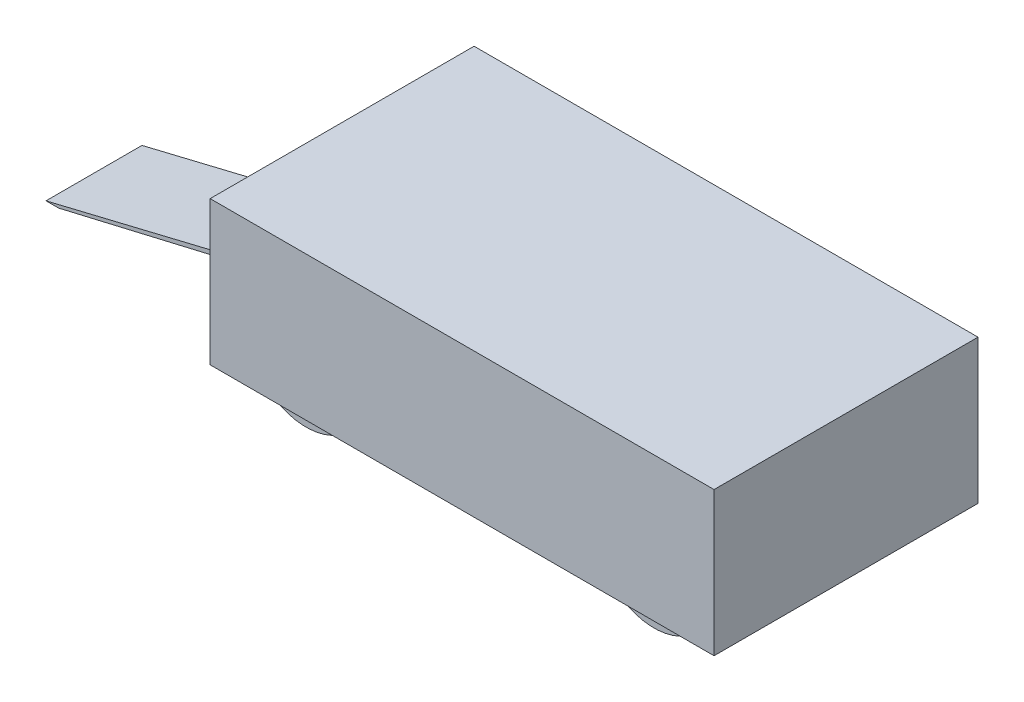
SolidWorks part; units mm, degrees
ref_plane "Front Plane" through (0, 0, 0) normal (0, 0, 1) x (1, 0, 0)
ref_plane "Top Plane" through (0, 0, 0) normal (0, 1, 0) x (1, 0, 0)
ref_plane "Right Plane" through (0, 0, 0) normal (1, 0, 0) x (0, 0, -1)
sketch "Chasis" plane through (0, 0, 0) normal (0, 1, 0) x (1, 0, 0)
  line L1 (-266.7, -139.7) -> (266.7, -139.7)
  line L2 (-266.7, -139.7) -> (-266.7, 139.7)
  line L3 (-266.7, 139.7) -> (266.7, 139.7)
  line L4 (266.7, -139.7) -> (266.7, 139.7)
  line L5 (-266.7, -139.7) -> (266.7, 139.7) construction
  line L6 (-266.7, 139.7) -> (266.7, -139.7) construction
  point P0 (0, 0)
  dimension "D1" = 533.4
  dimension "D2" = 279.4
extrude "Boss-Extrude1" add sketch "Chasis" along normal blind 152.4 contours L3 L4 L1 L2
ref_plane "Plane1" through (0, 38.1, 0) normal (0, -1, 0) x (-1, 0, 0)
sketch "Sketch3" plane through (0, 38.1, 0) normal (0, -1, 0) x (-1, 0, 0)
  line L0 (247.65, -69.85) -> (184.15, -69.85)
  line L1 (247.65, -69.85) -> (247.65, -120.65)
  line L2 (247.65, -120.65) -> (184.15, -120.65)
  line L3 (184.15, -69.85) -> (184.15, -120.65)
  line L4 (266.7, -139.7) -> (266.7, 139.7) construction
  line L5 (266.7, -139.7) -> (-266.7, -139.7) construction
  dimension "D1" = 63.5
  dimension "D2" = 50.8
  dimension "D3" = 19.05
  dimension "D4" = 19.05
revolve "Revolve2" add sketch "Sketch3" angle 360 about L3
mirror "Mirror1" about plane through (0, 0, 0) normal (0, 0, 1) of "Revolve2"
mirror "Mirror2" about plane through (0, 0, 0) normal (1, 0, 0) of "Mirror1", "Revolve2"
sketch "Sketch4" plane through (-266.7, 0, 0) normal (-1, 0, 0) x (0, 0, 1)
  line L0 (139.7, 152.4) -> (139.7, 0) construction
  line L1 (-50.8, 50.8) -> (50.8, 50.8)
  line L2 (-50.8, 50.8) -> (-50.8, 38.1)
  line L3 (-50.8, 38.1) -> (50.8, 38.1)
  line L4 (50.8, 50.8) -> (50.8, 38.1)
  line L6 (139.7, 0) -> (-139.7, 0) construction
  point P8 (50.8, 29.3696)
  point P9 (0, 0)
  point P10 (0, 0)
  dimension "D1" = 101.6
  dimension "D2" = 88.9
  dimension "D3" = 50.8
  dimension "D4" = 12.7
extrude "Cut-Extrude1" cut sketch "Sketch4" against normal blind 241.3
sketch "Sketch7" plane through (0, 0, -50.8) normal (0, 0, 1) x (1, 0, 0)
  line L0 (-266.7, 38.1) -> (-529.3594, -25.4)
  line L1 (-266.7, 38.1) -> (-266.7, 33.0276)
  line L2 (-266.7, 33.0276) -> (-515.9916, -25.4)
  line L3 (-515.9916, -25.4) -> (-529.3594, -25.4)
  arc A0 (-234.95, 0) -> (-133.35, 0) centre (-184.15, 38.1) ccw construction
  point P8 (-529.3594, -25.4)
extrude "Boss-Extrude2" add sketch "Sketch7" along normal up to surface (101.6 mm away) up to face at (-146.05, 44.45, 50.8)
